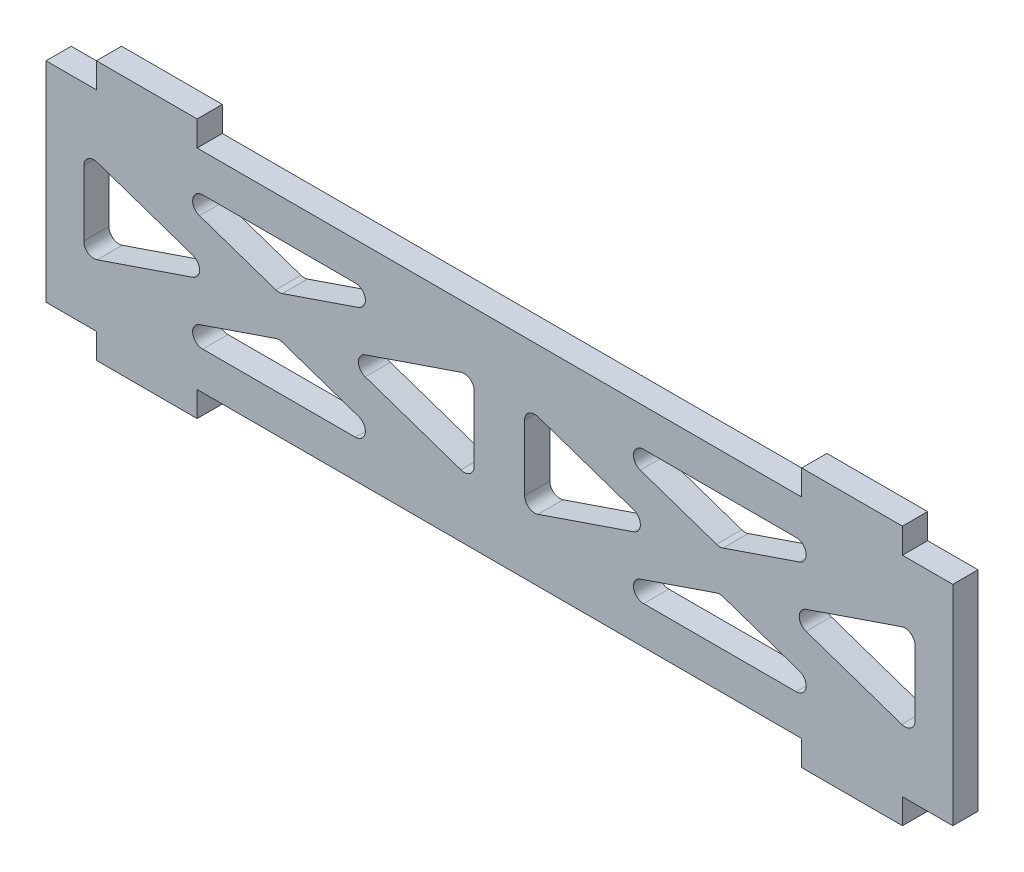
SolidWorks part; units mm, degrees
ref_plane "Front Plane" through (0, 0, 0) normal (0, 0, 1) x (1, 0, 0)
ref_plane "Top Plane" through (0, 0, 0) normal (0, 1, 0) x (1, 0, 0)
ref_plane "Right Plane" through (0, 0, 0) normal (1, 0, 0) x (0, 0, -1)
sketch "Sketch1" plane through (0, 0, 0) normal (0, 0, 1) x (1, 0, 0)
  line L0 (0, 0) -> (12.7, 0)
  line L1 (12.7, 0) -> (12.7, -6.35)
  line L2 (12.7, -6.35) -> (38.1, -6.35)
  line L3 (38.1, -6.35) -> (38.1, 0)
  line L4 (38.1, 0) -> (190.5, 0)
  line L5 (190.5, 0) -> (190.5, -6.35)
  line L6 (190.5, -6.35) -> (215.9, -6.35)
  line L7 (215.9, -6.35) -> (215.9, 0)
  line L8 (215.9, 0) -> (228.6, 0)
  line L9 (228.6, 0) -> (228.6, 52.72)
  line L10 (228.6, 26.36) -> (0, 26.36) construction
  line L11 (0, 52.72) -> (0, 0)
  line L12 (215.9, 52.72) -> (228.6, 52.72)
  line L13 (215.9, 59.07) -> (215.9, 52.72)
  line L14 (190.5, 59.07) -> (215.9, 59.07)
  line L15 (190.5, 52.72) -> (190.5, 59.07)
  line L16 (38.1, 52.72) -> (190.5, 52.72)
  line L17 (38.1, 59.07) -> (38.1, 52.72)
  line L18 (12.7, 59.07) -> (38.1, 59.07)
  line L19 (12.7, 52.72) -> (12.7, 59.07)
  line L20 (0, 52.72) -> (12.7, 52.72)
  line L21 (-38.1, 59.07) -> (349.25, 59.07) construction
  point P12 (228.6, 36.6944)
  point P14 (228.6, 32.9157)
  dimension "D1" = 12.7
  dimension "D2" = 6.35
  dimension "D3" = 25.4
  dimension "D4" = 152.4
  dimension "D5" = 12.7
extrude "Boss-Extrude1" add sketch "Sketch1" along normal blind 6.35
sketch "Sketch2" plane through (0, 0, 6.35) normal (0, 0, 1) x (1, 0, 0)
  line L0 (9.525, 43.195) -> (219.075, 43.195)
  line L1 (0, 52.72) -> (228.6, 52.72) construction
  line L2 (0, 52.72) -> (0, 0) construction
  line L3 (0, 0) -> (228.6, 0) construction
  line L4 (228.6, 52.72) -> (228.6, 0) construction
  line L5 (219.075, 43.195) -> (219.075, 9.525)
  line L6 (9.525, 9.525) -> (219.075, 9.525)
  line L7 (9.525, 43.195) -> (9.525, 9.525)
  line L8 (114.3, 52.72) -> (114.3, 0) construction
  line L9 (107.95, 52.72) -> (107.95, 0)
  line L10 (120.65, 52.72) -> (120.65, 0)
  line L11 (9.525, 43.195) -> (107.95, 9.525) construction
  line L12 (11.0665, 47.7011) -> (109.4915, 14.0311)
  line L13 (7.9835, 38.6889) -> (106.4085, 5.0189)
  line L14 (9.525, 9.525) -> (107.95, 43.195) construction
  line L15 (7.9835, 14.0311) -> (106.4085, 47.7011)
  line L16 (11.0665, 5.0189) -> (109.4915, 38.6889)
  line L17 (219.075, 43.195) -> (120.65, 9.525) construction
  line L18 (217.5335, 47.7011) -> (119.1085, 14.0311)
  line L19 (220.6165, 38.6889) -> (122.1915, 5.0189)
  line L20 (219.075, 9.525) -> (120.65, 43.195) construction
  line L21 (220.6165, 14.0311) -> (122.1915, 47.7011)
  line L22 (217.5335, 5.0189) -> (119.1085, 38.6889)
  arc A0 (11.0665, 47.7011) -> (7.9835, 38.6889) centre (9.525, 43.195) ccw
  arc A1 (106.4085, 5.0189) -> (109.4915, 14.0311) centre (107.95, 9.525) ccw
  arc A2 (7.9835, 14.0311) -> (11.0665, 5.0189) centre (9.525, 9.525) ccw
  arc A3 (109.4915, 38.6889) -> (106.4085, 47.7011) centre (107.95, 43.195) ccw
  arc A4 (217.5335, 47.7011) -> (220.6165, 38.6889) centre (219.075, 43.195) cw
  arc A5 (122.1915, 5.0189) -> (119.1085, 14.0311) centre (120.65, 9.525) cw
  arc A6 (220.6165, 14.0311) -> (217.5335, 5.0189) centre (219.075, 9.525) cw
  arc A7 (119.1085, 38.6889) -> (122.1915, 47.7011) centre (120.65, 43.195) cw
  point P16 (58.7375, 26.36)
  point P22 (58.7375, 26.36)
  point P28 (0, 0)
  point P30 (169.8625, 26.36)
  point P36 (169.8625, 26.36)
  dimension "D3" = 4.7625
  dimension "D2" = 12.7
  dimension "D1" = 9.525
extrude "Cut-Extrude1" cut sketch "Sketch2" against normal through all contours L7 L15 L13 | L12 L15 L0 | L16 L12 L9 | L16 L6 L13 | L18 L22 L10 | L21 L18 L0 | L21 L5 L19 | L6 L22 L19
fillet "Fillet1" radius 2.54 24 edges at (120.65, 14.5585, 3.175) (120.65, 38.1615, 3.175) (155.1486, 26.36, 3.175) (107.95, 38.1615, 3.175) (107.95, 14.5585, 3.175) (73.4514, 26.36, 3.175) (169.8625, 21.3265, 3.175) (204.3611, 9.525, 3.175) (135.3639, 9.525, 3.175) (184.5764, 26.36, 3.175) (219.075, 38.1615, 3.175) (219.075, 14.5585, 3.175) (44.0236, 26.36, 3.175) (9.525, 14.5585, 3.175) (9.525, 38.1615, 3.175) (135.3639, 43.195, 3.175) (204.3611, 43.195, 3.175) (169.8625, 31.3935, 3.175) (93.2361, 43.195, 3.175) (24.2389, 43.195, 3.175) (58.7375, 21.3265, 3.175) (93.2361, 9.525, 3.175) (24.2389, 9.525, 3.175) (58.7375, 31.3935, 3.175)
